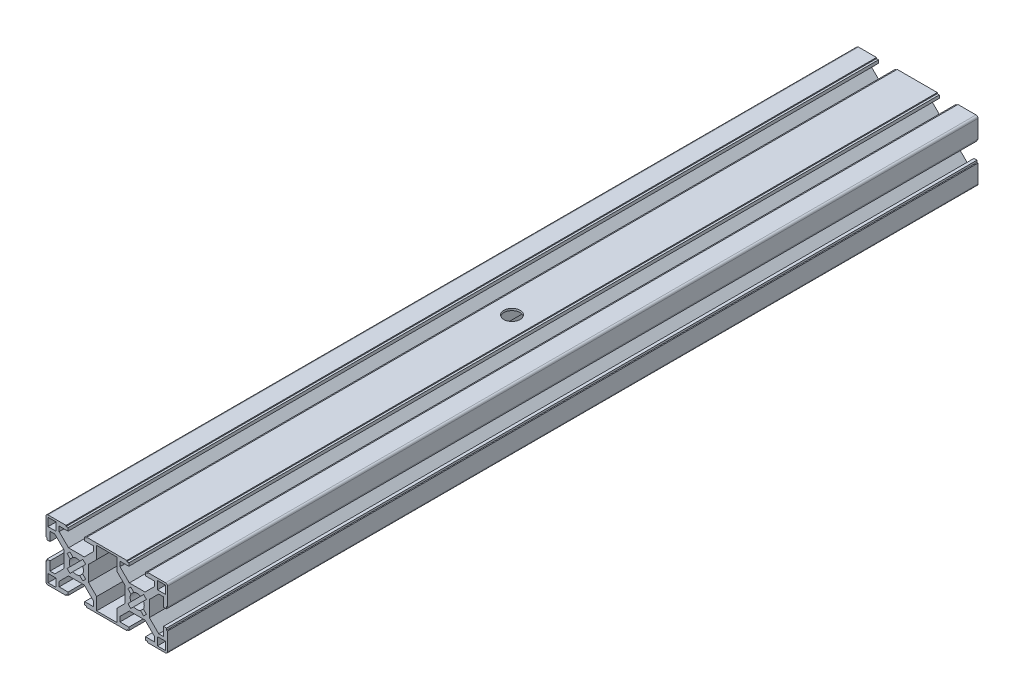
SolidWorks part; units mm, degrees
material "6063-T83"
ref_plane "Plano frontal" through (0, 0, 0) normal (0, 0, 1) x (1, 0, 0)
ref_plane "Plano superior" through (0, 0, 0) normal (0, 1, 0) x (1, 0, 0)
ref_plane "Plano direito" through (0, 0, 0) normal (1, 0, 0) x (0, 0, -1)
sketch "Esboço1" plane through (0, 0, 0) normal (0, 0, 1) x (1, 0, 0)
  line L5 (0, 0) -> (-17.7944, 17.7944) construction
  line L6 (0, 3.5) -> (0, 6)
  line L8 (0, 6) -> (-3.8787, 6)
  line L9 (-3.5, 0) -> (-6, 0)
  line L48 (-6, 0) -> (-6, 3.8787)
  line L49 (-3.8787, 6) -> (-8.5, 10.6213)
  line L50 (-6, 3.8787) -> (-10.6213, 8.5)
  line L51 (0, 0) -> (-12.921, 0) construction
  line L52 (-8.5, 13) -> (-4.1, 13)
  line L53 (-4.1, 13) -> (-4.1, 14.5)
  line L54 (-4.1, 14.5) -> (-5.1, 14.5)
  line L55 (-5.1, 14.5) -> (-5.1, 15)
  line L56 (-5.1, 15) -> (-15, 15)
  line L57 (-15, 5.1) -> (-15, 15)
  line L58 (-14.5, 5.1) -> (-15, 5.1)
  line L59 (-14.5, 4.1) -> (-14.5, 5.1)
  line L60 (-13, 4.1) -> (-14.5, 4.1)
  line L61 (-13, 8.5) -> (-13, 4.1)
  line L62 (-1.6646, 3.0788) -> (-3.182, 4.5962)
  line L63 (-3.0788, 1.6646) -> (-4.5962, 3.182)
  line L64 (-4.5962, 3.182) -> (-3.182, 4.5962)
  line L65 (-8.5, 13) -> (-8.5, 10.6213)
  line L66 (-10, 14) -> (-14, 14)
  line L67 (-10, 14) -> (-10, 10)
  line L68 (-10, 10) -> (-14, 10)
  line L69 (-14, 14) -> (-14, 10)
  line L70 (-10, 14) -> (-14, 10) construction
  line L71 (-10, 10) -> (-14, 14) construction
  line L72 (-13, 8.5) -> (-10.6213, 8.5)
  circle A1 centre (0, 0) radius 3.5
  point P25 (-12, 12)
  dimension "D5" = 10.9
  dimension "D9" = 5.5
  dimension "D10" = 2
  dimension "D11" = 4
  dimension "D12" = 4
  dimension "D13" = 1
  dimension "D1" = 7
  dimension "D2" = 6
  dimension "D3" = 3
  dimension "D4" = 9.9
  dimension "D6" = 0.5
  dimension "D7" = 1.5
  dimension "D8" = 15
  dimension "D14" = 6.5
extrude "Ressalto-extrusão1" add sketch "Esboço1" along normal blind 400 contours A1 L6 L8 L49 L65 L52 L53 L54 L55 L56 L57 L58 L59 L60 L61 L72 L50 L48 L9 L63 L64 L62 L69 L66 L67 L68
sketch "Esboço3" plane through (0, 0, 0) normal (1, 0, 0) x (0, 0, -1)
  line L0 (0, 0) -> (-1000, 0) construction
  dimension "D1" = 1000
pattern_circular "PadrãoCircular1" count 4 over 360 about axis through (0, 0, 0) along (0, 0, 1) of "Ressalto-extrusão1"
pattern_linear "Padrão linear1" count 2 spacing 30 along (1, 0, 0) of "Ressalto-extrusão1", "PadrãoCircular1"
sketch "Esboço4" plane through (0, 0, 0) normal (0, 0, -1) x (-1, 0, 0)
  line L0 (-20, 14) -> (-20, -14)
  line L1 (-20, -14) -> (-10, -14)
  line L2 (-10, -14) -> (-10, 14)
  line L3 (-10, 14) -> (-20, 14)
extrude "Corte-extrusão1" cut sketch "Esboço4" against normal through all
fillet "Filete1" radius 1 4 edges at (45, -15, 200) (45, 15, 200) (-15, 15, 200) (-15, -15, 200)
sketch "Esboço5" plane through (0, 15, 0) normal (0, 1, 0) x (1, 0, 0)
  line L0 (15, 0) -> (15, -400) construction
  line L1 (5.1, 0) -> (24.9, 0) construction
  line L2 (5.1, -400) -> (24.9, -400) construction
  circle A0 centre (15, -200) radius 4
  dimension "D1" = 8
extrude "Corte-extrusão2" cut sketch "Esboço5" against normal through all
